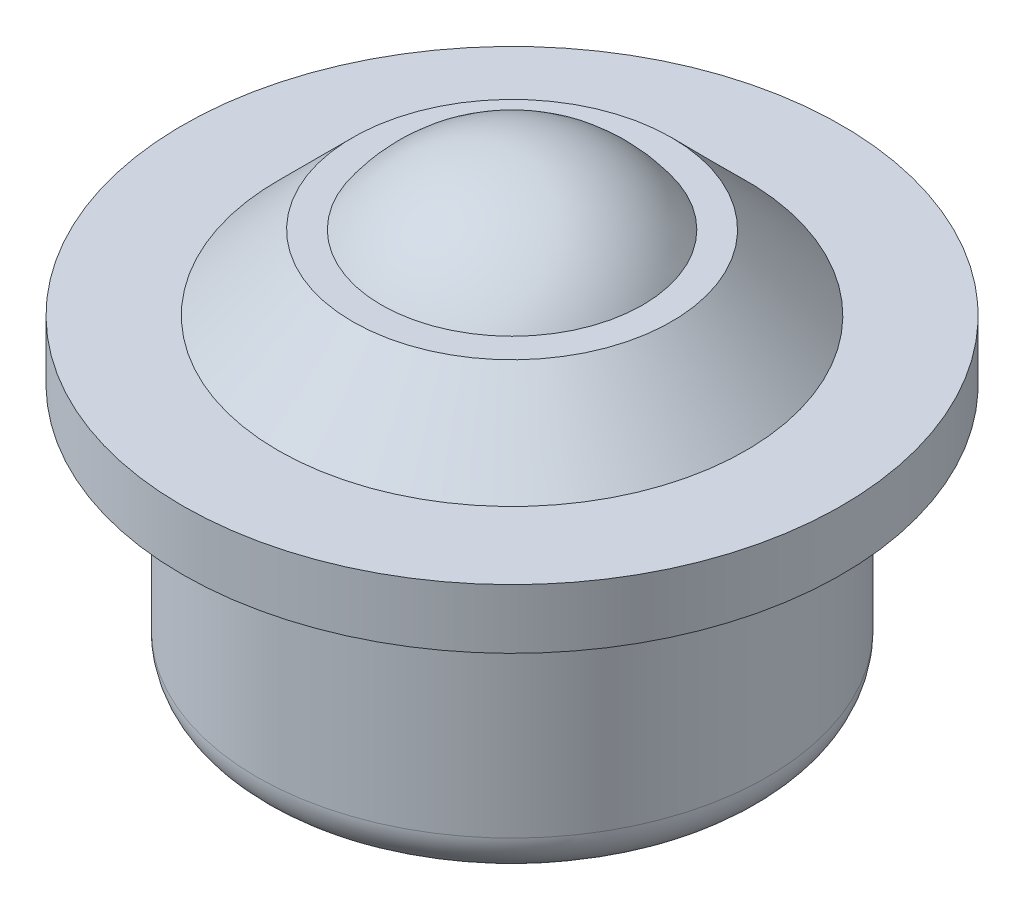
SolidWorks part; units mm, degrees
ref_plane "Plan de face" through (0, 0, 0) normal (0, 0, 1) x (1, 0, 0)
ref_plane "Plan de dessus" through (0, 0, 0) normal (0, 1, 0) x (1, 0, 0)
ref_plane "Plan de droite" through (0, 0, 0) normal (1, 0, 0) x (0, 0, -1)
sketch "Esquisse1" plane through (0, 0, 0) normal (0, 0, 1) x (1, 0, 0)
  line L0 (-10, -14) -> (0, -14) construction
  line L1 (-12, -2) -> (-15.5, -2)
  line L2 (-11, 0.8) -> (-15.5, 0.8)
  line L3 (-6.1449, 4.3) -> (-7.5, 4.3)
  line L4 (-15.5, 0.8) -> (-15.5, -2)
  line L5 (-12, -2) -> (-12, -12)
  line L6 (0, 7.5) -> (0, -14)
  line L7 (-7.5, 4.3) -> (-11, 0.8)
  arc A0 (0, 7.5) -> (-6.1449, 4.3) centre (0, 0) ccw
  arc A1 (-5.9909, -12.6534) -> (0, -14) centre (0, 0) ccw
  arc A2 (-12, -12) -> (-8.4234, -13.2305) centre (-10, -12) ccw
  arc A3 (-5.9909, -12.6534) -> (-8.4234, -13.2305) centre (-6.8467, -14.4611) ccw
  dimension "D1" = 15
  dimension "D2" = 9.5
  dimension "D5" = 21.5
  dimension "D9" = 4
  dimension "D10" = 2
  dimension "D12" = 7.5
  dimension "D3" = 6.3
  dimension "D4" = 2.8
  dimension "D6" = 15.5
  dimension "D7" = 12
  dimension "D8" = 1
  dimension "D11" = 45
revolve "Révolution1" add sketch "Esquisse1" angle 360 about L6
